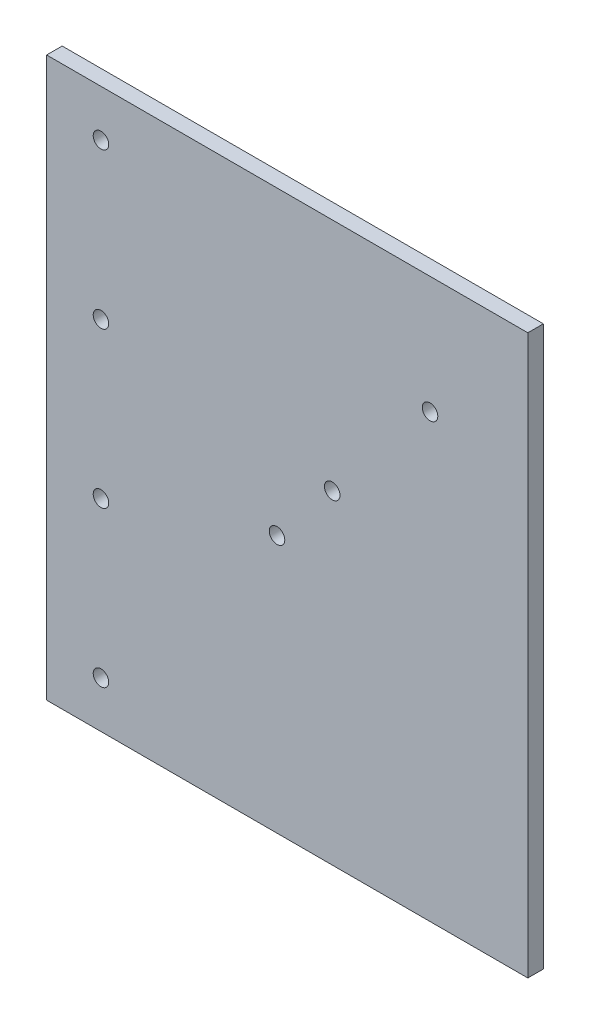
SolidWorks part; units mm, degrees
ref_plane "Front Plane" through (0, 0, 0) normal (0, 0, 1) x (1, 0, 0)
ref_plane "Top Plane" through (0, 0, 0) normal (0, 1, 0) x (1, 0, 0)
ref_plane "Right Plane" through (0, 0, 0) normal (1, 0, 0) x (0, 0, -1)
sketch "Sketch1" plane through (0, 0, 0) normal (0, 0, 1) x (1, 0, 0)
  line L1 (0, 0) -> (393.7, 0)
  line L2 (0, 0) -> (0, 457.2)
  line L3 (0, 457.2) -> (393.7, 457.2)
  line L4 (393.7, 0) -> (393.7, 457.2)
  dimension "D1" = 393.7
  dimension "D2" = 457.2
extrude "Plate" add sketch "Sketch1" along normal blind 12.7
hole_wizard "Hole" positions "Sketch4" profile "Sketch3" hole size "1/2" standard "Ansi Inch"
sketch "Sketch4" plane through (0, 0, 12.7) normal (0, 0, 1) x (1, 0, 0)
  line L0 (0, 457.2) -> (0, 0) construction
  line L1 (0, 0) -> (393.7, 0) construction
  point P0 (44.45, 38.1)
  dimension "D1" = 44.45
  dimension "D2" = 38.1
sketch "Sketch3" plane through (44.45, 38.1, 12.7) normal (1, 0, 0) x (0, -1, 0)
  line L0 (0, 0) -> (0, 29.2155)
  line L1 (0, 29.2155) -> (6.35, 25.4)
  line L2 (6.35, 25.4) -> (6.35, 0)
  line L5 (6.35, 0) -> (0, 0)
  line L10 (0, 29.2155) -> (-6.35, 25.4) construction
  line L11 (0, -6.35) -> (0, 107.95) construction
  dimension "Hole Dia." = 12.7
  dimension "Hole Depth" = 25.4
  dimension "Drill Angle" = 118
pattern_linear "Standard Linear" count 4 spacing 127 along (0, 1, 0) of "Hole"
sketch "Sketch5" plane through (0, 0, 12.7) normal (0, 0, 1) x (1, 0, 0)
  line L0 (44.45, 38.1) -> (393.7, 457.2) construction
  line L1 (393.7, 457.2) -> (0, 457.2) construction
  line L2 (393.7, 0) -> (393.7, 457.2) construction
  point P3 (233.6539, 265.1447)
  point P4 (313.677, 361.1723)
  point P9 (188.4915, 210.9498)
  dimension "D1" = 225
  dimension "D2" = 125
  dimension "D3" = 125
pattern_sketch "Sketch-Pattern1" of "Hole" driven by "Sketch5"
